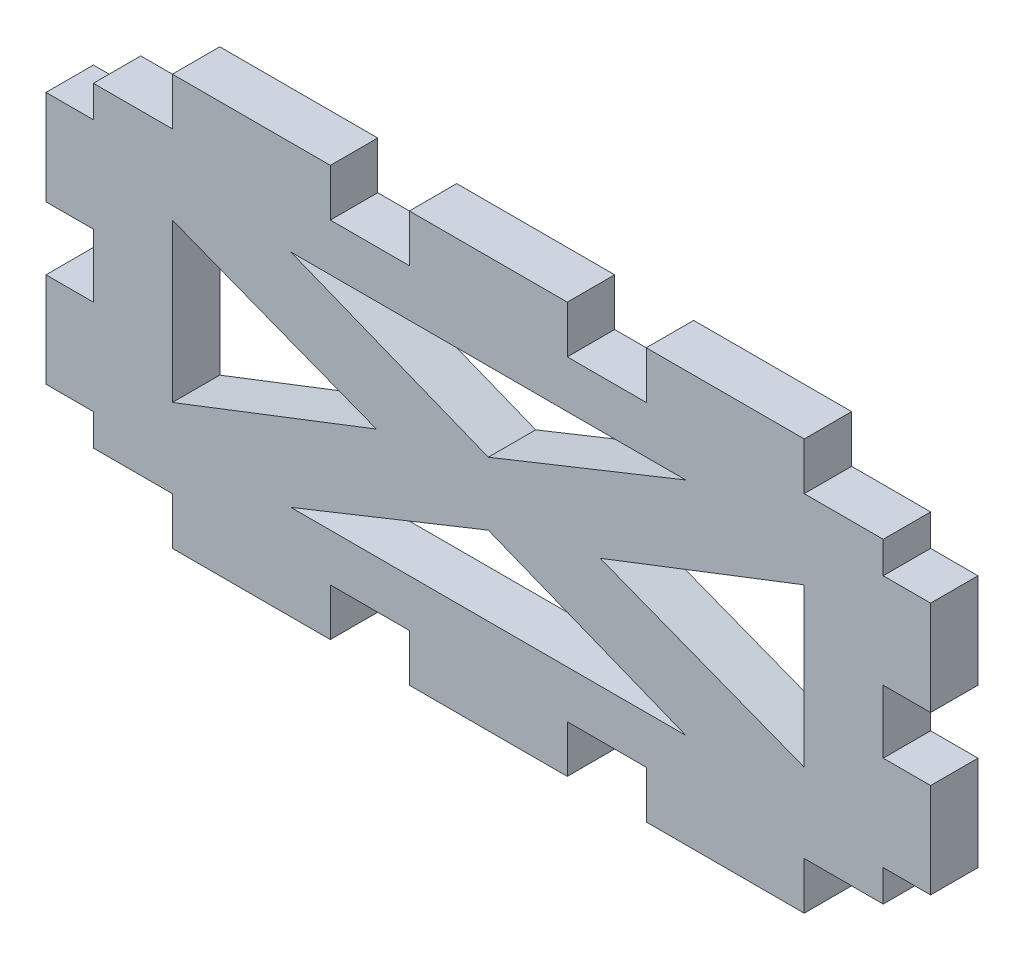
SolidWorks part; units mm, degrees
material "Thornel Mat VMA"
ref_plane "前视基准面" through (0, 0, 0) normal (0, 0, 1) x (1, 0, 0)
ref_plane "上视基准面" through (0, 0, 0) normal (0, 1, 0) x (1, 0, 0)
ref_plane "右视基准面" through (0, 0, 0) normal (1, 0, 0) x (0, 0, -1)
sketch "草图1" plane through (0, 0, 0) normal (0, 0, 1) x (1, 0, 0)
  line L0 (0, -55) -> (0, 55) construction
  line L1 (-25, -10) -> (-20, -10)
  line L2 (-25, -10) -> (-25, -8)
  line L3 (-25, 10) -> (-20, 10)
  line L4 (25, -10) -> (25, -8)
  line L5 (-25, 10) -> (25, -10) construction
  line L6 (25, 10) -> (-25, -10) construction
  line L7 (25, 8) -> (28, 8)
  line L9 (25, 2) -> (28, 2)
  line L10 (28, 8) -> (28, 2)
  line L11 (25, -8) -> (28, -8)
  line L13 (25, -2) -> (28, -2)
  line L14 (28, -8) -> (28, -2)
  line L15 (-25, -2) -> (-28, -2)
  line L16 (-28, -8) -> (-28, -2)
  line L17 (-25, -8) -> (-28, -8)
  line L19 (-25, 2) -> (-28, 2)
  line L20 (-28, 8) -> (-28, 2)
  line L21 (-25, 8) -> (-28, 8)
  line L23 (-5, 10) -> (-5, 13)
  line L25 (-20, 10) -> (-20, 13)
  line L26 (-20, 13) -> (-10, 13)
  line L27 (-10, 10) -> (-10, 13)
  line L29 (5, 10) -> (5, 13)
  line L30 (-5, 13) -> (5, 13)
  line L31 (10, 10) -> (10, 13)
  line L33 (20, 10) -> (20, 13)
  line L34 (10, 13) -> (20, 13)
  line L35 (-25, 8) -> (-25, 10)
  line L36 (-25, -2) -> (-25, 2)
  line L37 (-10, 10) -> (-5, 10)
  line L38 (5, 10) -> (10, 10)
  line L39 (20, 10) -> (25, 10)
  line L40 (25, 8) -> (25, 10)
  line L41 (25, -2) -> (25, 2)
  line L42 (55, 0) -> (-55, 0) construction
  line L43 (20, -10) -> (20, -13)
  line L44 (10, -13) -> (20, -13)
  line L45 (10, -10) -> (10, -13)
  line L46 (5, -10) -> (5, -13)
  line L47 (-5, -13) -> (5, -13)
  line L48 (-5, -10) -> (-5, -13)
  line L49 (-10, -10) -> (-10, -13)
  line L50 (-20, -13) -> (-10, -13)
  line L51 (-20, -10) -> (-20, -13)
  line L52 (-10, -10) -> (-5, -10)
  line L53 (5, -10) -> (10, -10)
  line L54 (20, -10) -> (25, -10)
  line L56 (-12.5, 7) -> (12.5, 7)
  line L57 (12.5, 7) -> (0, 2)
  line L58 (-12.5, 7) -> (0, 2)
  line L60 (20, 5) -> (20, -5)
  line L61 (20, -5) -> (7.0843, 0)
  line L62 (20, 5) -> (7.0843, 0)
  line L63 (-20, 5) -> (-7.0843, 0)
  line L64 (-20, -5) -> (-7.0843, 0)
  line L65 (-20, 5) -> (-20, -5)
  line L66 (-12.5, -7) -> (0, -2)
  line L67 (12.5, -7) -> (0, -2)
  line L68 (-12.5, -7) -> (12.5, -7)
  point P1 (0, 0)
  dimension "D1" = 50
  dimension "D2" = 20
  dimension "D3" = 3
  dimension "D4" = 6
  dimension "D5" = 3
  dimension "D6" = 2
  dimension "D7" = 6
  dimension "D8" = 2
  dimension "D9" = 3
  dimension "D10" = 5
  dimension "D11" = 10
  dimension "D13" = 3
  dimension "D12" = 3
extrude "凸台-拉伸1" add sketch "草图1" along normal blind 3
